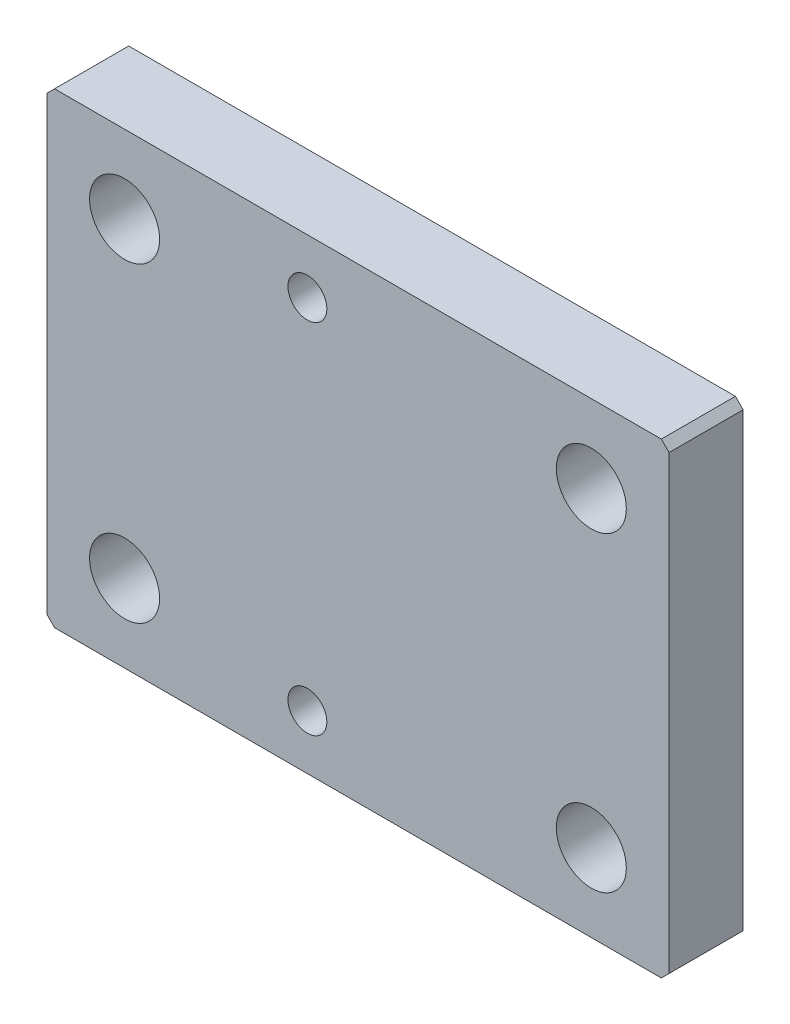
SolidWorks part; units mm, degrees
material "6061-T6 (SS)"
ref_plane "Front Plane" through (0, 0, 0) normal (0, 0, 1) x (1, 0, 0)
ref_plane "Top Plane" through (0, 0, 0) normal (0, 1, 0) x (1, 0, 0)
ref_plane "Right Plane" through (0, 0, 0) normal (1, 0, 0) x (0, 0, -1)
sketch "Sketch1" plane through (0, 0, 0) normal (0, 0, 1) x (1, 0, 0)
  line L1 (40, 30) -> (-40, 30)
  line L2 (40, 30) -> (40, -30)
  line L3 (40, -30) -> (-40, -30)
  line L4 (-40, 30) -> (-40, -30)
  line L5 (40, 30) -> (-40, -30) construction
  line L6 (40, -30) -> (-40, 30) construction
  line L7 (30, -20) -> (-30, -20) construction
  line L8 (30, -20) -> (30, 20) construction
  line L9 (30, 20) -> (-30, 20) construction
  line L10 (-30, -20) -> (-30, 20) construction
  line L11 (30, -20) -> (-30, 20) construction
  line L12 (30, 20) -> (-30, -20) construction
  line L13 (6.5, -23) -> (-6.5, -23) construction
  line L14 (6.5, -23) -> (6.5, 23) construction
  line L15 (6.5, 23) -> (-6.5, 23) construction
  line L16 (-6.5, -23) -> (-6.5, 23) construction
  line L17 (6.5, -23) -> (-6.5, 23) construction
  line L18 (6.5, 23) -> (-6.5, -23) construction
  point P0 (0, 0)
  point P6 (0, 0)
  point P11 (0, 0)
  dimension "D1" = 46
  dimension "D2" = 13
  dimension "D3" = 40
  dimension "D4" = 60
  dimension "D5" = 10
  dimension "D6" = 10
extrude "Boss-Extrude1" add sketch "Sketch1" along normal mid plane 9.525
hole_wizard "M8 Clearance Hole1" positions "Sketch2" profile "Sketch3" hole size "M8" standard "ANSI Metric" end condition up to next
sketch "Sketch2" plane through (0, 0, 4.7625) normal (0, 0, 1) x (1, 0, 0)
  point P0 (-30, 20)
  point P3 (30, 20)
  point P6 (30, -20)
  point P9 (-30, -20)
sketch "Sketch3" plane through (-30, 20, 4.7625) normal (1, 0, 0) x (0, -1, 0)
  line L0 (0, 0) -> (0, 9.525)
  line L1 (0, 9.525) -> (4.5, 9.525)
  line L2 (4.5, 9.525) -> (4.5, 0)
  line L5 (4.5, 0) -> (0, 0)
  line L11 (0, -6.35) -> (0, 107.95) construction
  dimension "Thru Hole Dia." = 9
  dimension "Thru Hole Depth" = 9.525
hole_wizard "M6x1.0 Tapped Hole2" positions "Sketch6" profile "Sketch7" tap size "M6x1.0" standard "ANSI Metric" end condition up to next
sketch "Sketch6" plane through (0, 0, 4.7625) normal (0, 0, 1) x (1, 0, 0)
  point P0 (-6.5, 23)
  point P3 (-6.5, -23)
sketch "Sketch7" plane through (-6.5, 23, 4.7625) normal (1, 0, 0) x (0, -1, 0)
  line L0 (0, 0) -> (0, 9.525)
  line L1 (0, 9.525) -> (2.5, 9.525)
  line L2 (2.5, 9.525) -> (2.5, 0)
  line L5 (2.5, 0) -> (0, 0)
  line L11 (0, -6.35) -> (0, 107.95) construction
  dimension "Thru Tap Drill Dia." = 5
  dimension "Thru Tap Drill Depth" = 9.525
cosmetic thread "Hole Thread5"
cosmetic thread "Hole Thread6"
hole_wizard "M6x1.0 Tapped Hole1" [suppressed] positions "Sketch4" profile "Sketch5" tap size "M6x1.0" standard "ANSI Metric"
sketch "Sketch4" plane through (0, 0, 4.7625) normal (0, 0, 1) x (1, 0, 0)
  point P0 (-6.5, 23)
  point P3 (6.5, 23)
  point P6 (6.5, -23)
  point P9 (-6.5, -23)
sketch "Sketch5" plane through (-6.5, 23, 4.7625) normal (1, 0, 0) x (0, -1, 0)
  line L0 (0, 0) -> (0, 9.525)
  line L1 (0, 9.525) -> (2.5, 9.525)
  line L2 (2.5, 9.525) -> (2.5, 0)
  line L5 (2.5, 0) -> (0, 0)
  line L11 (0, -6.35) -> (0, 107.95) construction
  dimension "Thru Tap Drill Dia." = 5
  dimension "Thru Tap Drill Depth" = 9.525
cosmetic thread "Hole Thread1" [suppressed] parameters "D2"=6
cosmetic thread "Hole Thread2" [suppressed] parameters "D2"=6
cosmetic thread "Hole Thread3" [suppressed] parameters "D2"=6
cosmetic thread "Hole Thread4" [suppressed] parameters "D2"=6
chamfer "Chamfer1" distance 1 4 edges at (-40, -30, 0) (40, -30, 0) (40, 30, 0) (-40, 30, 0)
